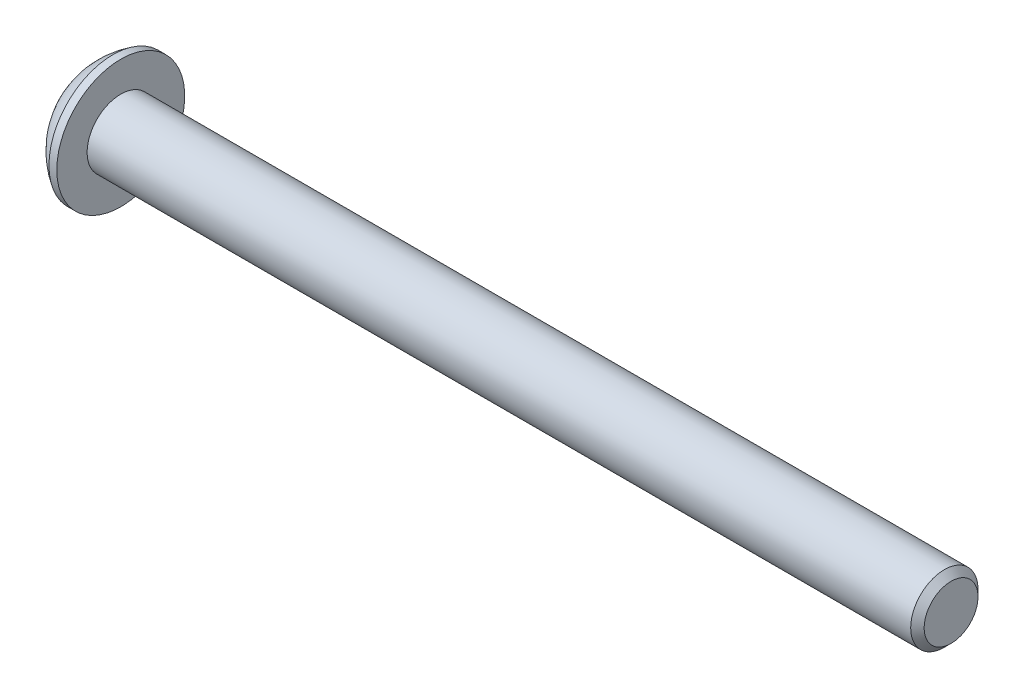
SolidWorks part; units mm, degrees
ref_plane "Front Plane" through (0, 0, 0) normal (0, 0, 1) x (1, 0, 0)
ref_plane "Top Plane" through (0, 0, 0) normal (0, 1, 0) x (1, 0, 0)
ref_plane "Right Plane" through (0, 0, 0) normal (1, 0, 0) x (0, 0, -1)
sketch "Sketch1" plane through (0, 0, 0) normal (0, 0, 1) x (1, 0, 0)
  line L0 (0, 1.43) -> (0, 0)
  line L1 (0, 0) -> (38.65, 0)
  line L2 (38.65, 0) -> (38.65, 1.5)
  line L3 (38.65, 1.5) -> (1.65, 1.5)
  line L4 (1.65, 1.5) -> (1.65, 2.85)
  line L5 (1.65, 2.85) -> (1.3, 2.85)
  arc A0 (1.3, 2.85) -> (0, 1.43) centre (3.132, -0.1322) ccw
  dimension "D7" = 3.5
  dimension "D1" = 0.35
  dimension "D2" = 1.65
  dimension "D3" = 2.85
  dimension "D4" = 1.5
  dimension "D5" = 37
  dimension "D6" = 1.43
revolve "Revolve1" add sketch "Sketch1" angle 360 about L1
chamfer "Chamfer1" distance 0.3 angle 45 1 edges at (38.65, 0, 1.5)
sketch "Sketch2" plane through (0, 0, 0) normal (-1, 0, 0) x (0, 0, 1)
  line L1 (0, 1.1547) -> (-1, 0.5774)
  line L2 (-1, 0.5774) -> (-1, -0.5774)
  line L3 (-1, -0.5774) -> (0, -1.1547)
  line L4 (0, -1.1547) -> (1, -0.5774)
  line L5 (1, -0.5774) -> (1, 0.5774)
  line L6 (1, 0.5774) -> (0, 1.1547)
  circle A0 centre (0, 0) radius 1 construction
  dimension "D1" = 2
extrude "Cut-Extrude1" cut sketch "Sketch2" against normal blind 1
